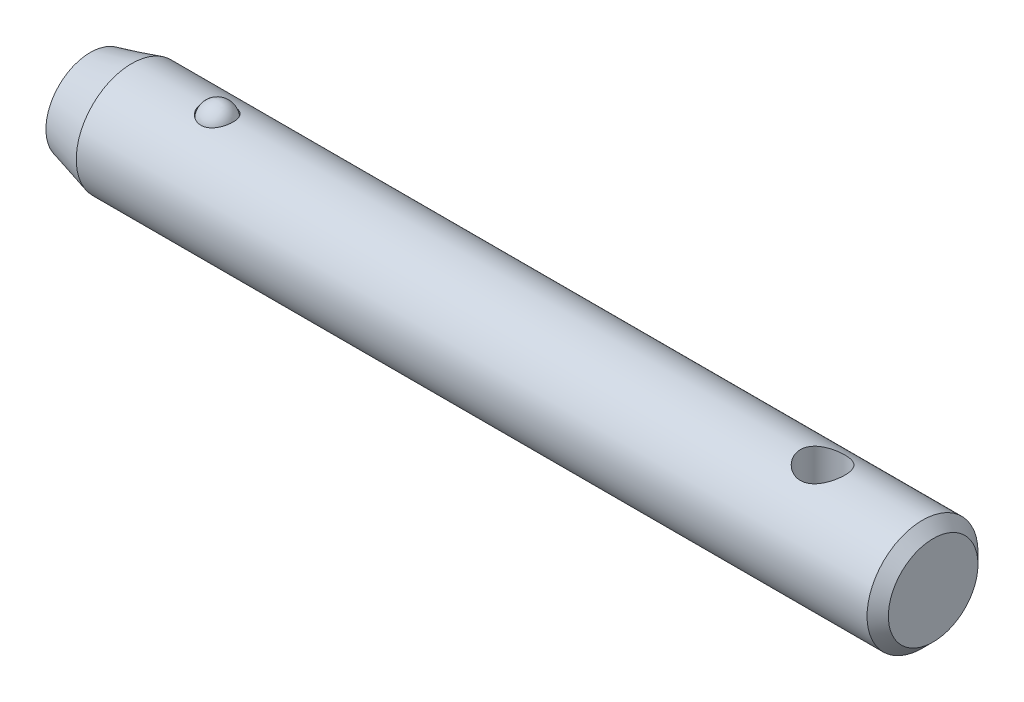
SolidWorks part; units mm, degrees
material "AISI 316 Annealed Stainless Steel Bar (SS)"
ref_plane "Front" through (0, 0, 0) normal (0, 0, 1) x (1, 0, 0)
ref_plane "Top" through (0, 0, 0) normal (0, 1, 0) x (1, 0, 0)
ref_plane "Right" through (0, 0, 0) normal (1, 0, 0) x (0, 0, -1)
ref_axis "Centre Axis" through (39.8114, 0, 0) along (-1, 0, 0)
sketch "Sketch1" plane through (0, 0, 0) normal (0, 0, 1) x (1, 0, 0)
  line L0 (15.0749, 1.6034) -> (14.6939, 1.9844)
  line L1 (14.6939, 1.9844) -> (15.0749, 1.9844) construction
  line L4 (15.0749, 1.6034) -> (15.0749, 0)
  line L5 (15.0749, 1.9844) -> (15.0749, 1.6034) construction
  line L6 (39.8114, 0) -> (-17.6885, 0) construction
  line L16 (14.6939, 1.9844) -> (-13.5937, 1.9844)
  line L17 (-15.0749, 1.9844) -> (-15.0749, 1.5875) construction
  line L19 (-13.5937, 1.9844) -> (-15.0749, 1.9844) construction
  line L22 (-15.0749, -1.9844) -> (-13.5937, -1.9844) construction
  line L23 (-10.5325, 1.7859) -> (-10.5325, -1.7859) construction
  line L24 (-15.0749, 0) -> (15.0749, 0)
  line L27 (15.0749, 0) -> (16.6783, 0) construction
  line L29 (-15.0749, 0) -> (-15.0749, -1.5875) construction
  line L36 (10.3251, 0) -> (10.3251, 1.9844) construction
  line L37 (-15.0749, 1.5875) -> (-15.0749, 0)
  line L38 (-13.5937, -1.9844) -> (15.0749, -1.9844) construction
  line L39 (-15.0749, -1.5875) -> (-15.0749, -1.9844) construction
  line L40 (-13.5937, 1.9844) -> (-15.0749, 1.5875)
  line L42 (-13.5937, -1.9844) -> (-15.0749, -1.5875) construction
  line L43 (-13.5937, 1.9844) -> (-13.5937, -1.9844) construction
  circle A2 centre (-10.5325, 1.7859) radius 0.5731 construction
  point P35 (-9.9949, 1.9844)
  dimension "A1" = 15
revolve "Revolve1" add sketch "Sketch1" angle 360 about axis through (39.8114, 0, 0) along (-1, 0, 0)
sketch "Sketch2" plane through (0, 0, 0) normal (0, 0, 1) x (1, 0, 0)
  line L0 (-9.934, 1.7859) -> (-11.131, 1.7859)
  line L1 (-10.5325, 2.359) -> (-10.5325, 2.3844) construction
  line L2 (-9.934, 1.7859) -> (-8.7371, 1.7859) construction
  circle A0 centre (-10.5325, 1.7859) radius 0.5731 construction
  circle A1 centre (-10.5325, 1.7859) radius 0.5731 construction
  arc A2 (-11.131, 1.7859) -> (-9.934, 1.7859) centre (-10.5325, 1.7859) cw
  dimension "D1" = 0.0254
revolve "Cut-Revolve1" cut sketch "Sketch2" angle 360 about L2
sketch "Sketch3" plane through (0, 0, 0) normal (0, 0, 1) x (1, 0, 0)
  line L0 (-9.9594, 1.7859) -> (-11.1056, 1.7859)
  line L1 (-9.9594, 1.7859) -> (-8.8133, 1.7859) construction
  circle A0 centre (-10.5325, 1.7859) radius 0.5731 construction
  arc A1 (-9.9594, 1.7859) -> (-11.1056, 1.7859) centre (-10.5325, 1.7859) ccw
revolve "Revolve2" add sketch "Sketch3" angle 360 about L1
sketch "Sketch4" plane through (0, 0, 0) normal (0, 0, 1) x (1, 0, 0)
  line L1 (11.1189, -1.9844) -> (11.9126, -1.9844)
  line L2 (11.1189, -1.9844) -> (11.1189, 1.9844)
  line L3 (11.1189, 1.9844) -> (11.9126, 1.9844)
  line L4 (11.9126, -1.9844) -> (11.9126, 1.9844)
  line L5 (11.1189, -1.9844) -> (11.1189, -2.7781) construction
  line L6 (11.9126, 1.9844) -> (15.0749, 1.9844) construction
  line L8 (10.3251, -1.9844) -> (10.3251, 1.9844) construction
  line L9 (10.3251, 0) -> (11.1189, 0) construction
  line L11 (11.1189, 0) -> (11.9126, 0) construction
  line L12 (14.6939, 1.9844) -> (-13.5937, 1.9844) construction
  line L14 (-13.5937, -1.9844) -> (15.0749, -1.9844) construction
  dimension "D1" = 1.5875
revolve "Cut-Revolve2" cut sketch "Sketch4" angle 360 about L2
sketch "Sketch5" plane through (0, 0, 0) normal (0, 0, 1) x (1, 0, 0)
  line L0 (0, 0) -> (10.2738, 0) construction
  line L1 (10.2738, 0) -> (10.2738, 1.9844) construction
  line L2 (14.6939, 1.9844) -> (-13.5937, 1.9844) construction
  line L3 (23.7358, 0) -> (37.1978, 0) construction
  line L4 (11.9126, 1.9844) -> (11.9639, 1.9844) construction
  line L5 (11.1189, 1.9844) -> (11.9126, 1.9844) construction
  line L6 (10.4209, 1.9844) -> (10.4209, -1.9844) construction
  line L7 (10.2738, 1.9844) -> (10.3251, 1.9844) construction
  line L8 (11.1189, -1.9844) -> (11.9126, -1.9844) construction
  line L9 (10.4209, -1.9844) -> (11.9126, -1.9844) construction
  line L10 (10.2738, 0) -> (23.7358, 0) construction
  line L12 (11.9639, 1.9844) -> (10.4209, 1.9844) construction
  line L13 (23.7358, 11.938) -> (23.7358, 13.462) construction
  circle A0 centre (23.7358, 0) radius 13.462
  circle A1 centre (23.7358, 0) radius 11.938 construction
  circle A2 centre (23.7358, 0) radius 12.7 construction
  point P26 (23.7358, 12.7)
curve "Helix/Spiral1" pitch 1.5494 height 1.3557 turns 0.875
sketch "Sketch6" plane through (114.0038, 0, 0) normal (0, 1, 0) x (0, 0, -1)
  line L0 (0, 102.206) -> (0, 102.968) construction
  line L1 (0, 102.968) -> (0, 103.73) construction
  circle A0 centre (0, 102.968) radius 0.762
  dimension "D1" = 1.524
sketch "Sketch7" plane through (0, 0, 0) normal (0, 0, 1) x (1, 0, 0)
  circle A0 centre (23.7358, 0) radius 13.462 construction
  circle A1 centre (23.7358, 0) radius 13.462
curve "Helix/Spiral2" pitch 1.5494 height 1.3557 turns 0.875
equation "\"D12@Sketch1\"=\"A@Sketch1\" * 0.80"
equation "\"D2@Sketch1\"=\"A@Sketch1\" * 0.9"
equation "\"D1@Sketch4\" = \"A@Sketch1\" / 2.5"
equation "\"Ring OD@Sketch5\" = \"R Ring Dia@Sketch5\" * 0.06"
equation "\"D4@Helix/Spiral1\"=\"Ring OD@Sketch5\" + 0.001"
equation "\"D1@Sketch6\"=\"Ring OD@Sketch5\""
equation "\"D4@Helix/Spiral2\" = \"D4@Helix/Spiral1\""
equation "\"D5@Helix/Spiral2\" = \"D5@Helix/Spiral1\""
